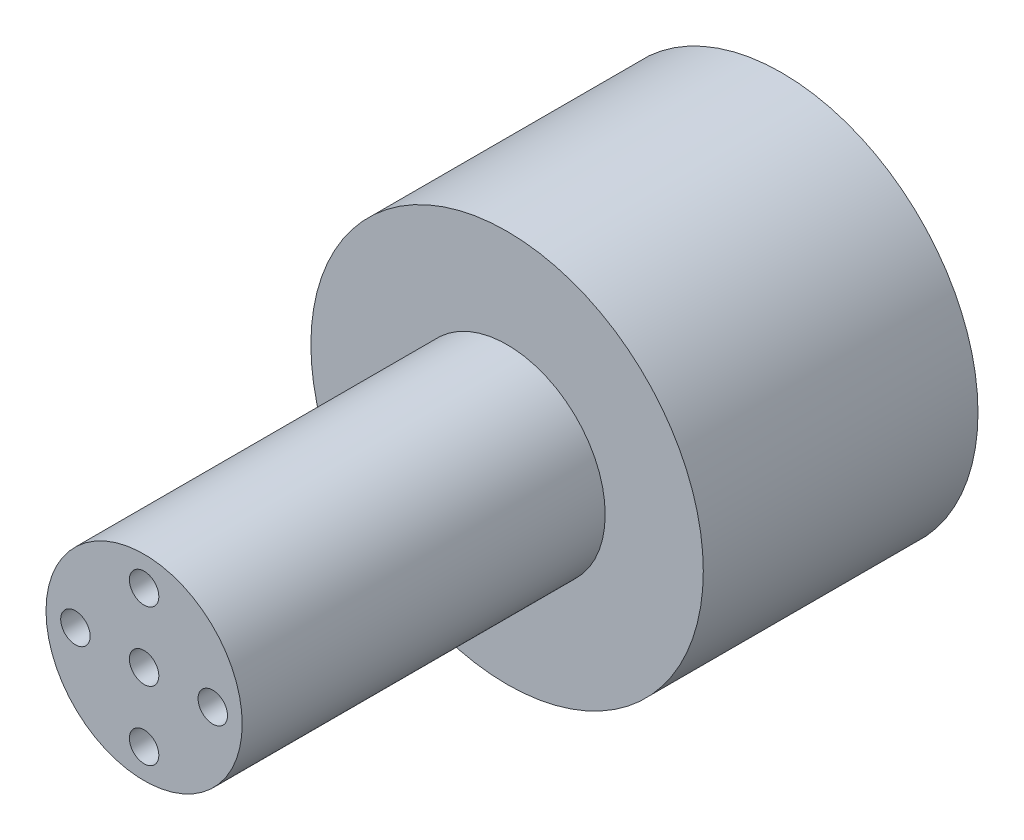
SolidWorks part; units mm, degrees
ref_plane "前视基准面" through (0, 0, 0) normal (0, 0, 1) x (1, 0, 0)
ref_plane "上视基准面" through (0, 0, 0) normal (0, 1, 0) x (1, 0, 0)
ref_plane "右视基准面" through (0, 0, 0) normal (1, 0, 0) x (0, 0, -1)
sketch "草图1" plane through (0, 0, 0) normal (0, 0, 1) x (1, 0, 0)
  circle A0 centre (0, 0) radius 10
  dimension "D1" = 20
extrude "凸台-拉伸1" add sketch "草图1" along normal blind 65
ref_plane "基准面1" through (-10, 0, 0) normal (-1, 0, 0) x (0, 0, 1)
sketch "草图2" plane through (-10, 0, 0) normal (-1, 0, 0) x (0, 0, 1)
  line L0 (30.5, 0) -> (35.55, 0) construction
  line L1 (30.5, 2.5) -> (35.55, 2.5)
  line L2 (30.5, -2.5) -> (35.55, -2.5)
  arc A0 (30.5, 2.5) -> (30.5, -2.5) centre (30.5, 0) ccw
  arc A1 (35.55, -2.5) -> (35.55, 2.5) centre (35.55, 0) ccw
  point P3 (33.025, 0)
  dimension "D2" = 2.5
  dimension "D1" = 30.5
  dimension "D3" = 5.05
extrude "切除-拉伸1" cut sketch "草图2" against normal blind 2.5
sketch "草图3" plane through (0, 0, 0) normal (0, 0, -1) x (-1, 0, 0)
  circle A0 centre (0, 0) radius 20
  dimension "D1" = 40
extrude "凸台-拉伸2" add sketch "草图3" against normal blind 28
sketch "草图4" plane through (0, 0, 65) normal (0, 0, 1) x (1, 0, 0)
  circle A1 centre (0, 7) radius 1.5
  circle A3 centre (7, 0) radius 1.5
  circle A5 centre (0, -7) radius 1.5
  circle A6 centre (0, 0) radius 7 construction
  circle A7 centre (-7, 0) radius 1.5
  dimension "D1" = 14
  dimension "D2" = 3
  dimension "D3" = 4
extrude "切除-拉伸2" cut sketch "草图4" against normal blind 10
sketch "草图5" plane through (0, 0, 65) normal (0, 0, 1) x (1, 0, 0)
  circle A0 centre (0, 0) radius 1.5
  dimension "D1" = 3
extrude "切除-拉伸3" cut sketch "草图5" against normal blind 10
